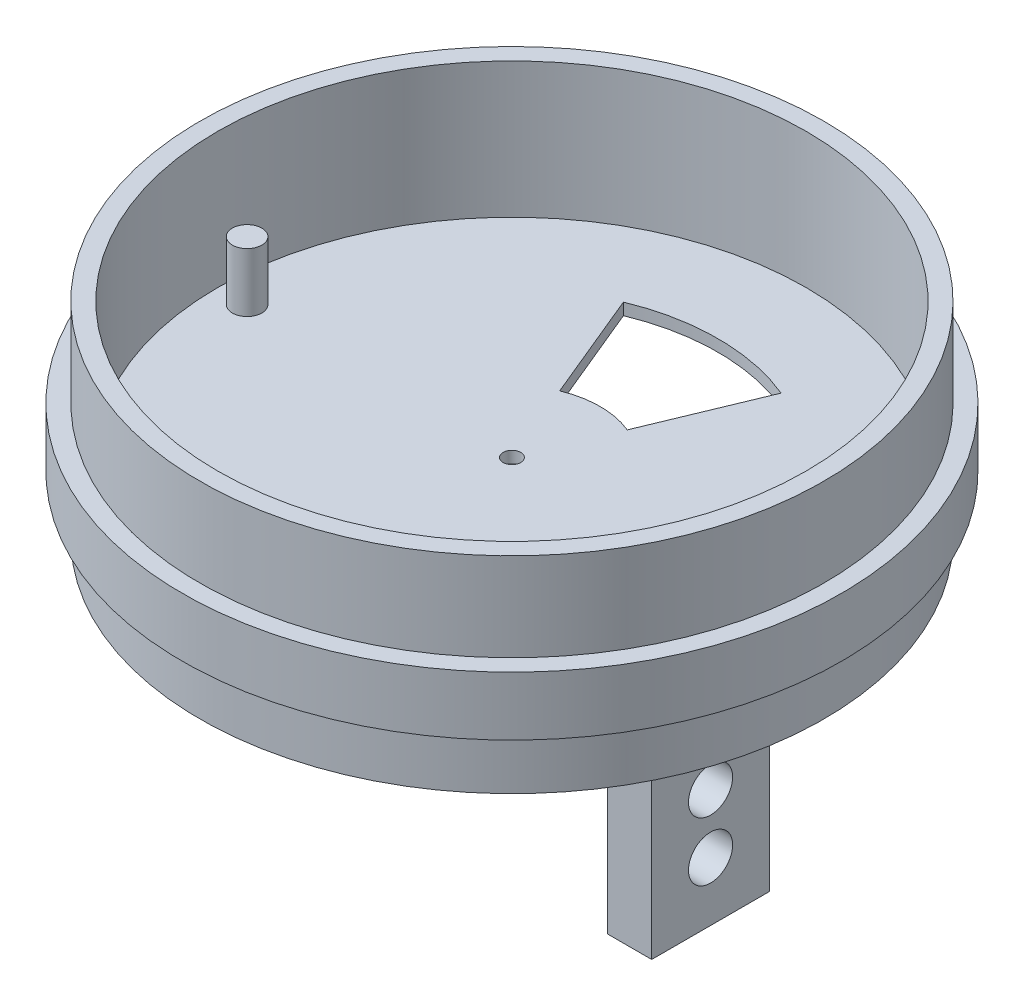
SolidWorks part; units mm, degrees
ref_plane "Front Plane" through (0, 0, 0) normal (0, 0, 1) x (1, 0, 0)
ref_plane "Top Plane" through (0, 0, 0) normal (0, 1, 0) x (1, 0, 0)
ref_plane "Right Plane" through (0, 0, 0) normal (1, 0, 0) x (0, 0, -1)
sketch "Sketch4" plane through (0, 0, 0) normal (1, 0, 0) x (0, 0, -1)
  line L0 (0, 0) -> (50, 0)
  line L1 (56, 0) -> (56, 10)
  line L2 (56, 10) -> (53, 10)
  line L3 (53, 10) -> (53, 25)
  line L4 (53, 25) -> (50, 25)
  line L5 (50, 25) -> (50, 2)
  line L6 (50, 2) -> (0, 2)
  line L7 (0, 2) -> (0, 0)
  line L8 (0, 0) -> (0, 44.4663) construction
  line L9 (53, 0) -> (56, 0)
  line L11 (50, 0) -> (50, -10)
  line L12 (50, -10) -> (53, -10)
  line L13 (53, 0) -> (53, -10)
  dimension "D1" = 15
  dimension "D2" = 10
  dimension "D3" = 2
  dimension "D4" = 10
  dimension "D5" = 3
  dimension "D6" = 3
  dimension "D7" = 56
revolve "Revolve2" add sketch "Sketch4" angle 360 about L8
sketch "Sketch5" plane through (0, 2, 0) normal (0, 1, 0) x (1, 0, 0)
  circle A0 centre (-45, 0) radius 2.5
  dimension "D1" = 5
  dimension "D2" = 45
extrude "Boss-Extrude2" add sketch "Sketch5" along normal blind 10 contours A0
pattern_circular "CirPattern2" count 2 over 360 about axis through (0.1128, 0, 0) along (0, 1, 0) of "Boss-Extrude2"
sketch "Sketch6" plane through (0, 2, 0) normal (0, 1, 0) x (1, 0, 0)
  line L0 (0, 0) -> (-13.3939, 32.3358) construction
  line L1 (-5.7403, 13.8582) -> (-13.3939, 32.3358)
  line L2 (13.3939, 32.3358) -> (5.7403, 13.8582)
  line L3 (-13.3939, 32.3358) -> (13.3939, 32.3358) construction
  line L4 (0, 0) -> (13.3939, 32.3358) construction
  arc A0 (-13.3939, 32.3358) -> (13.3939, 32.3358) centre (0, 0) cw
  arc A1 (-5.7403, 13.8582) -> (5.7403, 13.8582) centre (0, 0) cw
  point P6 (0, 32.3358)
  dimension "D1" = 35
  dimension "D2" = 15
  dimension "D3" = 45
extrude "Cut-Extrude4" cut sketch "Sketch6" against normal up to next contours L2 A1 L1 A0
sketch "Sketch7" plane through (0, 2, 0) normal (0, 1, 0) x (1, 0, 0)
  circle A0 centre (0, 0) radius 1.5
  dimension "D1" = 3
extrude "Cut-Extrude5" cut sketch "Sketch7" against normal through all
sketch "Sketch10" plane through (0, 0, 0) normal (0, -1, 0) x (1, 0, 0)
  line L0 (1.5, 0) -> (57.3941, 0) construction
  line L1 (0, 0) -> (0, 11.7619) construction
  line L2 (26.25, 10) -> (33.75, 10)
  line L3 (26.25, 10) -> (26.25, -10)
  line L4 (26.25, -10) -> (33.75, -10)
  line L5 (33.75, 10) -> (33.75, -10)
  line L6 (26.25, 10) -> (33.75, -10) construction
  line L7 (26.25, -10) -> (33.75, 10) construction
  point P1 (30, 0)
  dimension "D1" = 7.5
  dimension "D2" = 20
  dimension "D3" = 30
extrude "Boss-Extrude3" add sketch "Sketch10" along normal blind 50 contours L3 L2 L5 L4
sketch "Sketch11" plane through (26.25, 0, 0) normal (-1, 0, 0) x (0, 0, 1)
  line L0 (10, 0) -> (-10, 0) construction
  line L1 (0, 0) -> (0, -3.9611) construction
  circle A0 centre (0, -10) radius 3.75
  dimension "D1" = 7.5
  dimension "D2" = 10
extrude "Cut-Extrude6" cut sketch "Sketch11" against normal up to next
pattern_linear "LPattern1" count 4 spacing 10 along (0, -1, 0) of "Cut-Extrude6"
mirror "Mirror1" about plane through (0, 0, 0) normal (1, 0, 0) of "Cut-Extrude6", "Boss-Extrude3", "LPattern1"
fillet "Fillet1" radius 2.5 8 edges at (-30, 0, 10) (-26.25, 0, 0) (-33.75, 0, 0) (-30, 0, -10) (30, 0, -10) (26.25, 0, 0) (30, 0, 10) (33.75, 0, 0)
